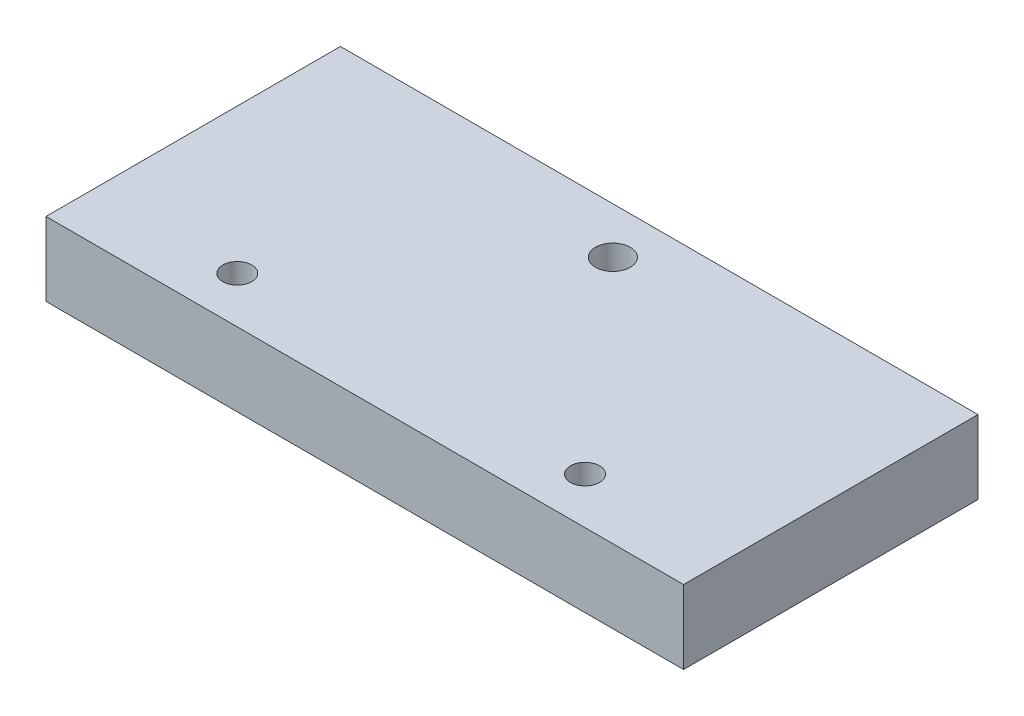
SolidWorks part; units mm, degrees
material "Aleación 1060"
ref_plane "Alzado" through (0, 0, 0) normal (0, 0, 1) x (1, 0, 0)
ref_plane "Planta" through (0, 0, 0) normal (0, 1, 0) x (1, 0, 0)
ref_plane "Vista lateral" through (0, 0, 0) normal (1, 0, 0) x (0, 0, -1)
sketch "Croquis1" plane through (0, 0, 0) normal (0, 1, 0) x (1, 0, 0)
  line L1 (55, -25.4) -> (-55, -25.4)
  line L2 (55, -25.4) -> (55, 25.4)
  line L3 (55, 25.4) -> (-55, 25.4)
  line L4 (-55, -25.4) -> (-55, 25.4)
  line L5 (55, -25.4) -> (-55, 25.4) construction
  line L6 (55, 25.4) -> (-55, -25.4) construction
  point P0 (0, 0)
  dimension "D1" = 50.8
  dimension "D2" = 110
extrude "Saliente-Extruir1" add sketch "Croquis1" along normal blind 12.7
sketch "Croquis3" plane through (0, 12.7, 0) normal (0, 1, 0) x (1, 0, 0)
  line L0 (-55, -17.4) -> (55, -17.4) construction
  line L1 (-55, 25.4) -> (-55, -25.4) construction
  line L2 (55, -25.4) -> (55, 25.4) construction
  line L3 (-55, -25.4) -> (55, -25.4) construction
  line L4 (55, 25.4) -> (-55, 25.4) construction
  circle A0 centre (-30, -17.4) radius 2.5
  circle A1 centre (30, -17.4) radius 2.5
  circle A2 centre (0, 17.4) radius 3
  point P17 (0, 0)
  dimension "D2" = 5
  dimension "D3" = 5
  dimension "D6" = 6
  dimension "D1" = 8
  dimension "D4" = 60
  dimension "D5" = 30
  dimension "D7" = 8
extrude "Cortar-Extruir1" cut sketch "Croquis3" against normal blind 12.7
